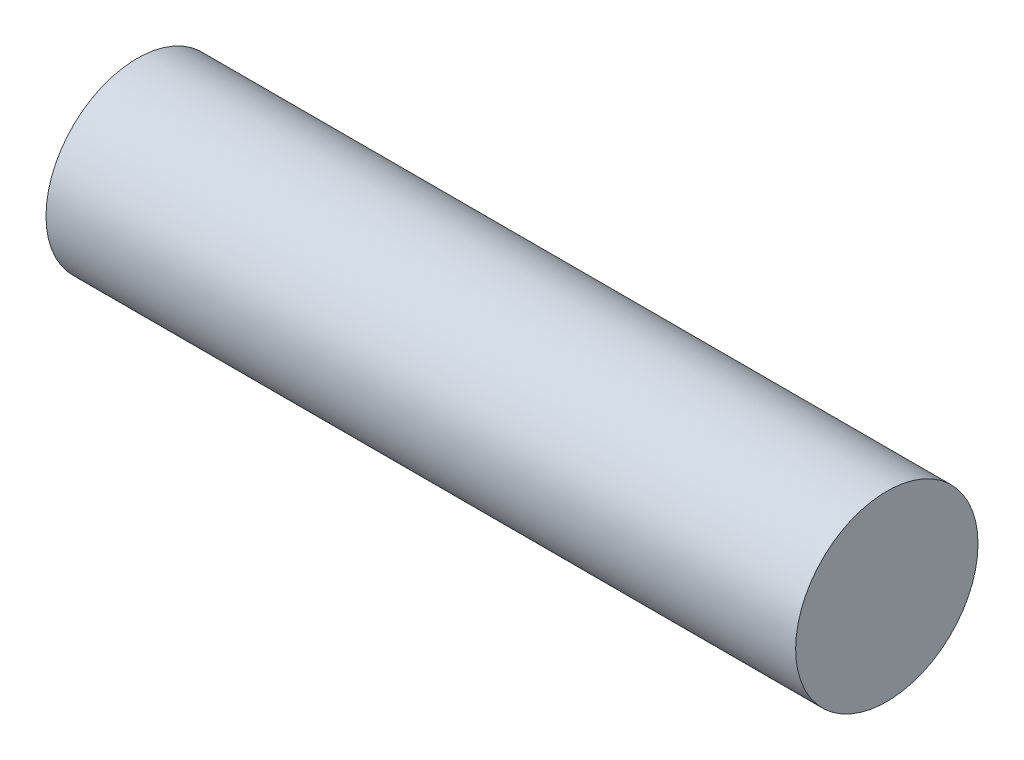
SolidWorks part; units mm, degrees
material "Commercialement pur CP-Ti UNS R50400 (SS)"
ref_plane "Plan de face" through (0, 0, 0) normal (0, 0, 1) x (1, 0, 0)
ref_plane "Plan de dessus" through (0, 0, 0) normal (0, 1, 0) x (1, 0, 0)
ref_plane "Plan de droite" through (0, 0, 0) normal (1, 0, 0) x (0, 0, -1)
sketch "Esquisse1" plane through (0, 0, 0) normal (1, 0, 0) x (0, 0, -1)
  circle A0 centre (0, 0) radius 90
  dimension "D1" = 180
extrude "Boss.-Extru.1" add sketch "Esquisse1" along normal blind 740
